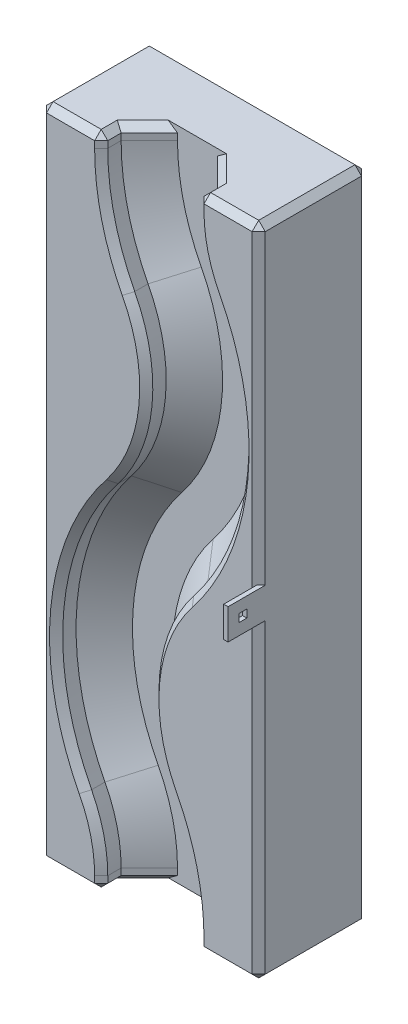
SolidWorks part; units mm, degrees
ref_plane "Front" through (0, 0, 0) normal (0, 0, 1) x (1, 0, 0)
ref_plane "Top" through (0, 0, 0) normal (0, 1, 0) x (1, 0, 0)
ref_plane "Right" through (0, 0, 0) normal (1, 0, 0) x (0, 0, -1)
sketch "Sketch1" plane through (0, 0, 0) normal (0, 0, 1) x (1, 0, 0)
  line L1 (0, 0) -> (50, 0)
  line L2 (0, 0) -> (0, 150)
  line L3 (0, 150) -> (50, 150)
  line L4 (50, 0) -> (50, 150)
  dimension "D1" = 50
  dimension "D2" = 150
extrude "Boss-Extrude1" add sketch "Sketch1" along normal blind 25
sketch "Sketch2" plane through (0, 0, 0) normal (0, -1, 0) x (1, 0, 0)
  line L0 (0, 25) -> (50, 25) construction
  line L1 (29.5563, 36) -> (20.4437, 36)
  line L2 (20.4437, 36) -> (14, 29.5563)
  line L3 (14, 29.5563) -> (14, 20.4437)
  line L4 (14, 20.4437) -> (20.4437, 14)
  line L5 (20.4437, 14) -> (29.5563, 14)
  line L6 (29.5563, 14) -> (36, 20.4437)
  line L7 (36, 20.4437) -> (36, 29.5563)
  line L8 (36, 29.5563) -> (29.5563, 36)
  circle A0 centre (25, 25) radius 11 construction
  dimension "D1" = 22
sketch "Sketch3" plane through (0, 0, 25) normal (0, 0, 1) x (1, 0, 0)
  line L0 (25, 0) -> (25, 3)
  line L1 (25, 147) -> (25, 150)
  line L2 (50, 150) -> (0, 150) construction
  line L3 (0, 75) -> (50, 75) construction
  line L4 (0, 150) -> (0, 0) construction
  line L5 (50, 0) -> (50, 150) construction
  arc A0 (25, 3) -> (20.0752, 23.227) centre (-19, 3) ccw
  arc A1 (20.0752, 23.227) -> (25, 75) centre (62.7026, 45.2929) cw
  arc A2 (25, 75) -> (29.9248, 126.773) centre (-12.7026, 104.7071) ccw
  arc A3 (29.9248, 126.773) -> (25, 147) centre (69, 147) cw
  point P11 (25, 150)
  dimension "D2" = 44
  dimension "D3" = 48
  dimension "D1" = 3
sweep "Cut-Sweep1" cut profiles "Sketch2" path "Sketch3"
chamfer "Chamfer1" distance 1.5 angle 45 34 edges at (14, 148.5, 25) (36, 148.5, 25) (15.5612, 133.9888, 25) (36.9367, 139.1933, 25) (24.1311, 101.2034, 25) (46.0323, 99.1201, 25) (3.9677, 50.8799, 25) (25.8689, 48.7966, 25) (13.0633, 10.8067, 25) (34.4388, 16.0112, 25) (17.2218, 150, 17.2218) (14, 150, 22.7218) (32.7782, 150, 17.2218) (36, 150, 22.7218) (50, 150, 12.5) (43, 150, 25) (7, 150, 25) (0, 75, 0) (25, 150, 0) (0, 150, 12.5) (0, 75, 25) (14, 1.5, 25) (17.2218, 0, 17.2218) (14, 0, 22.7218) (7, 0, 25) (0, 0, 12.5) (36, 1.5, 25) (32.7782, 0, 17.2218) (36, 0, 22.7218) (43, 0, 25) (50, 75, 25) (50, 75, 0) (50, 0, 12.5) (25, 0, 0)
sketch "Sketch4" plane through (0, 0, 25) normal (0, 0, 1) x (1, 0, 0)
  line L0 (50, 148.5) -> (50, 1.5) construction
  line L1 (50, 71.5) -> (49, 71.5)
  line L2 (50, 71.5) -> (50, 78.5)
  line L3 (50, 78.5) -> (49, 78.5)
  line L4 (49, 71.5) -> (49, 78.5)
  point P6 (50, 75)
  dimension "D1" = 7
  dimension "D2" = 1
extrude "Boss-Extrude2" add sketch "Sketch4" along normal blind 7 and the other way blind 10
sketch "Sketch5" plane through (50, 0, 0) normal (1, 0, 0) x (0, 0, -1)
  line L0 (-32, 71.5) -> (-32, 78.5) construction
  line L1 (-29.5, 74.1) -> (-27.7, 74.1)
  line L2 (-29.5, 74.1) -> (-29.5, 75.9)
  line L3 (-29.5, 75.9) -> (-27.7, 75.9)
  line L4 (-27.7, 74.1) -> (-27.7, 75.9)
  line L5 (-29.5, 75) -> (-32, 75) construction
  dimension "D1" = 1.8
  dimension "D2" = 2.5
extrude "Cut-Extrude1" cut sketch "Sketch5" against normal blind 7
